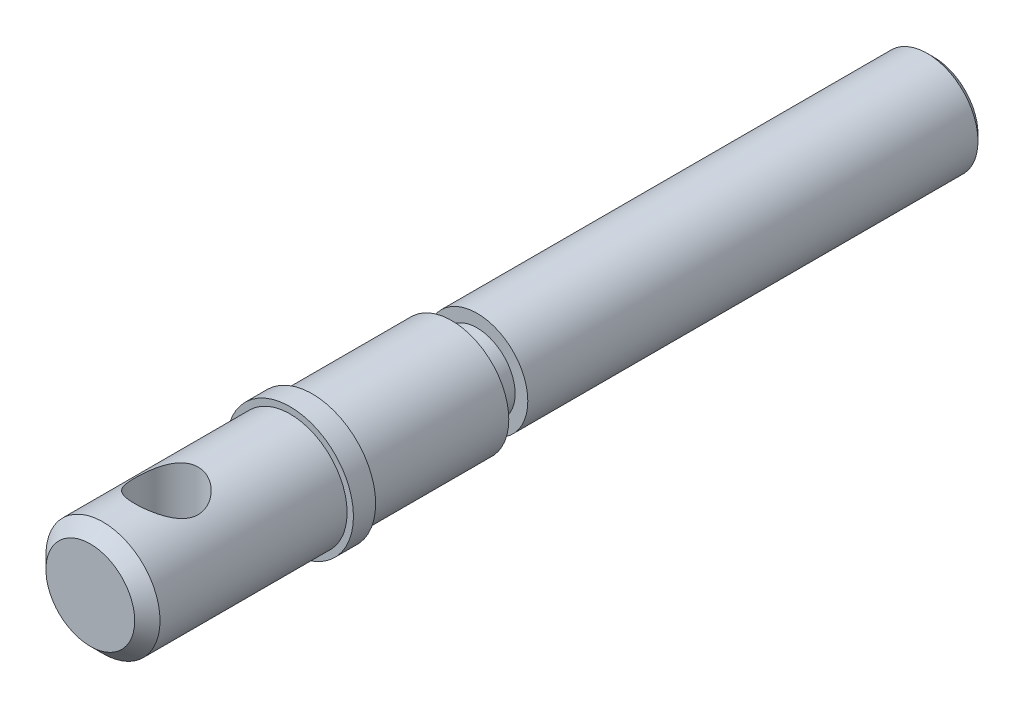
SolidWorks part; units mm, degrees
material "1.7225 (42CrMo4)"
ref_plane "Front Plane" through (0, 0, 0) normal (0, 0, 1) x (1, 0, 0)
ref_plane "Top Plane" through (0, 0, 0) normal (0, 1, 0) x (1, 0, 0)
ref_plane "Right Plane" through (0, 0, 0) normal (1, 0, 0) x (0, 0, -1)
sketch "Esquisse2" plane through (0, 0, 0) normal (0, 0, 1) x (1, 0, 0)
  circle A0 centre (0, 0) radius 8
  dimension "D1" = 16
extrude "Boss.-Extru.1" add sketch "Esquisse2" along normal blind 72
cosmetic thread "Représentation de filetage1" parameters "D2"=13.797
sketch "Esquisse3" plane through (0, 0, 72) normal (0, 0, 1) x (1, 0, 0)
  circle A0 centre (0, 0) radius 6
  dimension "D1" = 12
extrude "Boss.-Extru.2" add sketch "Esquisse3" along normal blind 4
sketch "Esquisse4" plane through (0, 0, 76) normal (0, 0, 1) x (1, 0, 0)
  circle A0 centre (0, 0) radius 9
  dimension "D1" = 18
extrude "Boss.-Extru.3" add sketch "Esquisse4" along normal blind 22
sketch "Esquisse5" plane through (0, 0, 98) normal (0, 0, 1) x (1, 0, 0)
  circle A0 centre (0, 0) radius 10
  dimension "D1" = 20
extrude "Boss.-Extru.4" add sketch "Esquisse5" along normal blind 3.5
sketch "Esquisse6" plane through (0, 0, 101.5) normal (0, 0, 1) x (1, 0, 0)
  circle A0 centre (0, 0) radius 9
  dimension "D1" = 18
extrude "Boss.-Extru.5" add sketch "Esquisse6" along normal blind 31.5
chamfer "Chanfrein1" distance 2 angle 45 1 edges at (9, 0, 133)
chamfer "Chanfrein2" distance 1 angle 45 1 edges at (8, 0, 0)
sketch "Esquisse7" plane through (0, 0, 0) normal (0, 1, 0) x (1, 0, 0)
  line L0 (-7, -133) -> (7, -133) construction
  line L1 (9, -131) -> (9, -101.5) construction
  circle A0 centre (0, -121) radius 5
  dimension "D1" = 10
  dimension "D2" = 12
  dimension "D3" = 9
extrude "Enlèv. mat.-Extru.1" cut sketch "Esquisse7" against normal through all both and the other way through all
